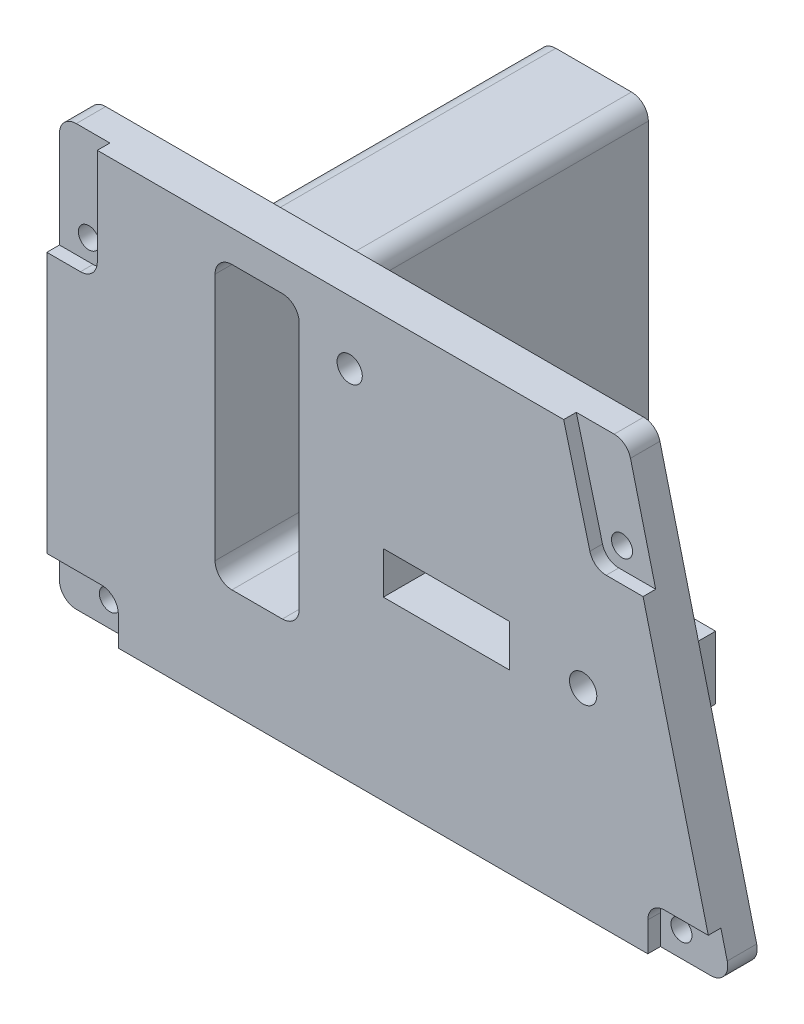
SolidWorks part; units mm, degrees
ref_plane "Front Plane" through (0, 0, 0) normal (0, 0, 1) x (1, 0, 0)
ref_plane "Top Plane" through (0, 0, 0) normal (0, 1, 0) x (1, 0, 0)
ref_plane "Right Plane" through (0, 0, 0) normal (1, 0, 0) x (0, 0, -1)
sketch "Sketch1" plane through (0, 0, 0) normal (0, 0, 1) x (1, 0, 0)
  line L0 (117.9439, -49.7664) -> (112.8411, -44.6636)
  line L1 (-38.0561, 50.2336) -> (89.8208, 50.2336)
  line L2 (-42.0561, 46.2336) -> (-42.0561, -45.7664)
  line L3 (-38.0561, -49.7664) -> (112.8208, -49.7664)
  line L5 (93.7014, 47.2038) -> (116.7014, -44.7962)
  arc A0 (89.8208, 50.2336) -> (93.7014, 47.2038) centre (89.8208, 46.2336) cw
  arc A1 (116.7014, -44.7962) -> (112.8208, -49.7664) centre (112.8208, -45.7664) cw
  arc A2 (-42.0561, -45.7664) -> (-38.0561, -49.7664) centre (-38.0561, -45.7664) ccw
  arc A3 (-42.0561, 46.2336) -> (-38.0561, 50.2336) centre (-38.0561, 46.2336) cw
  point P7 (92.9439, 50.2336)
  point P13 (-42.0561, -49.7664)
  point P16 (-42.0561, 50.2336)
  dimension "D4" = 4
  dimension "D1" = 160
  dimension "D2" = 100
  dimension "D3" = 135
extrude "Boss-Extrude1" add sketch "Sketch1" along normal blind 10
sketch "Sketch2" plane through (0, 0, 10) normal (0, 0, 1) x (1, 0, 0)
  line L0 (-42.0561, 46.2336) -> (-42.0561, -45.7664) construction
  line L1 (-2.0561, 42.7336) -> (17.9439, 42.7336)
  line L2 (-2.0561, 42.7336) -> (-2.0561, -24.2664)
  line L3 (-2.0561, -24.2664) -> (17.9439, -24.2664)
  line L4 (17.9439, 42.7336) -> (17.9439, -24.2664)
  line L5 (-38.0561, 50.2336) -> (89.8208, 50.2336) construction
  line L7 (37.9439, 2.2336) -> (67.9439, 2.2336)
  line L8 (37.9439, 2.2336) -> (37.9439, -7.7664)
  line L9 (37.9439, -7.7664) -> (67.9439, -7.7664)
  line L10 (67.9439, 2.2336) -> (67.9439, -7.7664)
  circle A0 centre (29.9439, 35.2336) radius 3
  dimension "D5" = 6
  dimension "D1" = 20
  dimension "D2" = 67
  dimension "D3" = 40
  dimension "D4" = 7.5
  dimension "D6" = 72
  dimension "D7" = 15
  dimension "D8" = 30
  dimension "D9" = 10
  dimension "D10" = 48
  dimension "D11" = 110
extrude "Cut-Extrude1" cut sketch "Sketch2" against normal blind 10
fillet "Fillet1" radius 4 4 edges at (-2.0561, -24.2664, 5) (17.9439, -24.2664, 5) (-2.0561, 42.7336, 5) (17.9439, 42.7336, 5)
sketch "Sketch4" plane through (0, 0, 0) normal (0, 0, -1) x (-1, 0, 0)
  line L0 (-17.9439, -20.2664) -> (-17.9439, 38.7336) construction
  line L1 (-16.9439, 45.7336) -> (1.0561, 45.7336)
  line L2 (-20.9439, 41.7336) -> (-20.9439, -23.2664)
  line L3 (-16.9439, -27.2664) -> (1.0561, -27.2664)
  line L4 (5.0561, 41.7336) -> (5.0561, -23.2664)
  line L5 (2.0561, 38.7336) -> (2.0561, -20.2664) construction
  line L6 (-1.9439, -24.2664) -> (-13.9439, -24.2664) construction
  line L7 (-13.9439, 42.7336) -> (-1.9439, 42.7336) construction
  line L9 (-1.9439, -24.2664) -> (-13.9439, -24.2664)
  line L10 (2.0561, -20.2664) -> (2.0561, 38.7336)
  line L11 (-1.9439, 42.7336) -> (-13.9439, 42.7336)
  line L12 (-17.9439, -20.2664) -> (-17.9439, 38.7336)
  arc A0 (-20.9439, -23.2664) -> (-16.9439, -27.2664) centre (-16.9439, -23.2664) ccw
  arc A1 (1.0561, -27.2664) -> (5.0561, -23.2664) centre (1.0561, -23.2664) ccw
  arc A2 (5.0561, 41.7336) -> (1.0561, 45.7336) centre (1.0561, 41.7336) ccw
  arc A3 (-16.9439, 45.7336) -> (-20.9439, 41.7336) centre (-16.9439, 41.7336) ccw
  arc A4 (-17.9439, -20.2664) -> (-13.9439, -24.2664) centre (-13.9439, -20.2664) ccw
  arc A5 (-1.9439, -24.2664) -> (2.0561, -20.2664) centre (-1.9439, -20.2664) ccw
  arc A6 (2.0561, 38.7336) -> (-1.9439, 42.7336) centre (-1.9439, 38.7336) ccw
  arc A7 (-13.9439, 42.7336) -> (-17.9439, 38.7336) centre (-13.9439, 38.7336) ccw
  dimension "D5" = 4
  dimension "D10" = 4
  dimension "D1" = 3
  dimension "D2" = 3
  dimension "D3" = 3
  dimension "D4" = 3
  dimension "D6" = 0
  dimension "D7" = 0
  dimension "D8" = 0
  dimension "D9" = 0
extrude "Boss-Extrude2" add sketch "Sketch4" along normal blind 70
sketch "Sketch6" plane through (0, 0, 10) normal (0, 0, 1) x (1, 0, 0)
  line L0 (-38.0561, 50.2336) -> (89.8208, 50.2336) construction
  line L1 (-42.0561, 50.2336) -> (-30.0561, 50.2336)
  line L2 (-42.0561, 50.2336) -> (-42.0561, 23.2336)
  line L3 (-42.0561, 23.2336) -> (-34.0561, 23.2336)
  line L4 (-30.0561, 50.2336) -> (-30.0561, 27.2336)
  line L5 (-42.0561, 46.2336) -> (-42.0561, -45.7664) construction
  line L6 (-38.0561, -49.7664) -> (112.8208, -49.7664) construction
  line L7 (-25.0561, -49.7664) -> (-42.0561, -49.7664)
  line L8 (-25.0561, -49.7664) -> (-25.0561, -42.7664)
  line L9 (-29.0561, -38.7664) -> (-42.0561, -38.7664)
  line L10 (-42.0561, -49.7664) -> (-42.0561, -38.7664)
  line L11 (80.8208, 50.2336) -> (87.044, 26.2298)
  line L12 (100.8208, -49.7664) -> (116.8208, -49.7664)
  line L13 (100.8208, -49.7664) -> (100.8208, -42.7664)
  line L14 (104.8208, -38.7664) -> (116.8208, -38.7664)
  line L15 (116.8208, -49.7664) -> (116.8208, -38.7664)
  line L16 (80.8208, 50.2336) -> (99.8208, 50.2336)
  line L18 (90.916, 23.2336) -> (99.8208, 23.2336)
  line L19 (99.8208, 50.2336) -> (99.8208, 23.2336)
  arc A0 (-34.0561, 23.2336) -> (-30.0561, 27.2336) centre (-34.0561, 27.2336) ccw
  arc A1 (-25.0561, -42.7664) -> (-29.0561, -38.7664) centre (-29.0561, -42.7664) ccw
  arc A2 (112.8208, -49.7664) -> (116.7014, -44.7962) centre (112.8208, -45.7664) ccw construction
  arc A3 (100.8208, -42.7664) -> (104.8208, -38.7664) centre (104.8208, -42.7664) cw
  arc A4 (93.7014, 47.2038) -> (89.8208, 50.2336) centre (89.8208, 46.2336) ccw construction
  arc A5 (87.044, 26.2298) -> (90.916, 23.2336) centre (90.916, 27.2336) ccw
  point P18 (-25.0561, -38.7664)
  point P28 (100.8208, -38.7664)
  point P38 (87.8208, 23.2336)
  dimension "D5" = 4
  dimension "D8" = 4
  dimension "D12" = 4
  dimension "D17" = 4
  dimension "D1" = 0
  dimension "D2" = 0
  dimension "D3" = 27
  dimension "D4" = 12
  dimension "D6" = 11
  dimension "D7" = 17
  dimension "D9" = 4
  dimension "D10" = 11
  dimension "D11" = 16
  dimension "D13" = 10
  dimension "D14" = 27
  dimension "D15" = 19
  dimension "D16" = 12
extrude "Cut-Extrude5" cut sketch "Sketch6" against normal blind 3
sketch "Sketch7" plane through (0, 0, 7) normal (0, 0, 1) x (1, 0, 0)
  line L0 (100.8208, -42.7664) -> (100.8208, -49.7664) construction
  line L1 (115.1939, -38.7664) -> (104.8208, -38.7664) construction
  line L2 (-25.0561, -49.7664) -> (-25.0561, -42.7664) construction
  line L3 (-29.0561, -38.7664) -> (-42.0561, -38.7664) construction
  line L4 (-42.0561, 23.2336) -> (-34.0561, 23.2336) construction
  line L7 (-30.0561, 27.2336) -> (-30.0561, 50.2336) construction
  line L8 (90.916, 23.2336) -> (99.6939, 23.2336) construction
  line L10 (80.8208, 50.2336) -> (87.044, 26.2298) construction
  circle A0 centre (91.6898, 28.2336) radius 2.5
  circle A1 centre (-35.0561, 28.2336) radius 2.5
  circle A2 centre (105.8208, -43.7664) radius 2.5
  circle A3 centre (-30.0561, -43.7664) radius 2.5
  dimension "D1" = 5
  dimension "D2" = 5
  dimension "D3" = 5
  dimension "D4" = 5
  dimension "D5" = 5
  dimension "D6" = 5
  dimension "D7" = 5
  dimension "D8" = 5
  dimension "D9" = 5
  dimension "D10" = 5
  dimension "D11" = 5
  dimension "D12" = 5
extrude "Cut-Extrude6" cut sketch "Sketch7" against normal blind 7
ref_plane "Plane1" through (-1.0561, 45.7336, -70) normal (1, 0, 0) x (0, 0, -1)
sketch "Sketch8" plane through (-1.0561, 45.7336, -70) normal (1, 0, 0) x (0, 0, -1)
  line L2 (-70, -69) -> (-70, -4) construction
  line L3 (0, -69) -> (-70, -69) construction
  circle A1 centre (-55, -36.5) radius 3.5
  dimension "D1" = 7
  dimension "D2" = 15
  dimension "D3" = 32.5
extrude "Cut-Extrude8" cut sketch "Sketch8" along normal blind 30 from offset 5 offset against normal yes
sketch "Sketch9" plane through (0, 0, 0) normal (0, 0, -1) x (-1, 0, 0)
  line L0 (-67.9439, -7.7664) -> (-67.9439, 2.2336) construction
  line L1 (-96.9439, 4.7336) -> (-92.9439, 4.7336)
  line L2 (-96.9439, 4.7336) -> (-96.9439, -10.2664)
  line L3 (-96.9439, -10.2664) -> (-92.9439, -10.2664)
  line L4 (-92.9439, 4.7336) -> (-92.9439, -10.2664)
  line L5 (-37.9439, -7.7664) -> (-67.9439, -7.7664) construction
  dimension "D1" = 4
  dimension "D2" = 25
  dimension "D3" = 15
  dimension "D4" = 2.5
extrude "Boss-Extrude3" add sketch "Sketch9" along normal blind 10
sketch "Sketch10" plane through (92.9439, 0, 0) normal (-1, 0, 0) x (0, 0, 1)
  line L0 (-10, -10.2664) -> (0, -10.2664) construction
  line L1 (-10, 4.7336) -> (-6, 4.7336)
  line L2 (-10, 4.7336) -> (-10, -10.2664)
  line L3 (-10, -10.2664) -> (-6, -10.2664)
  line L4 (-6, 4.7336) -> (-6, -10.2664)
  dimension "D1" = 4
extrude "Boss-Extrude4" add sketch "Sketch10" along normal blind 16.5
sketch "Sketch5" plane through (0, 0, 10) normal (0, 0, 1) x (1, 0, 0)
  line L2 (67.9439, -7.7664) -> (67.9439, 2.2336) construction
  line L3 (67.9439, 2.2336) -> (37.9439, 2.2336) construction
  circle A0 centre (85.4439, -2.7664) radius 3.25
  dimension "D3" = 6.5
  dimension "D1" = 17.5
  dimension "D2" = 5
extrude "Cut-Extrude10" cut sketch "Sketch5" against normal blind 20
